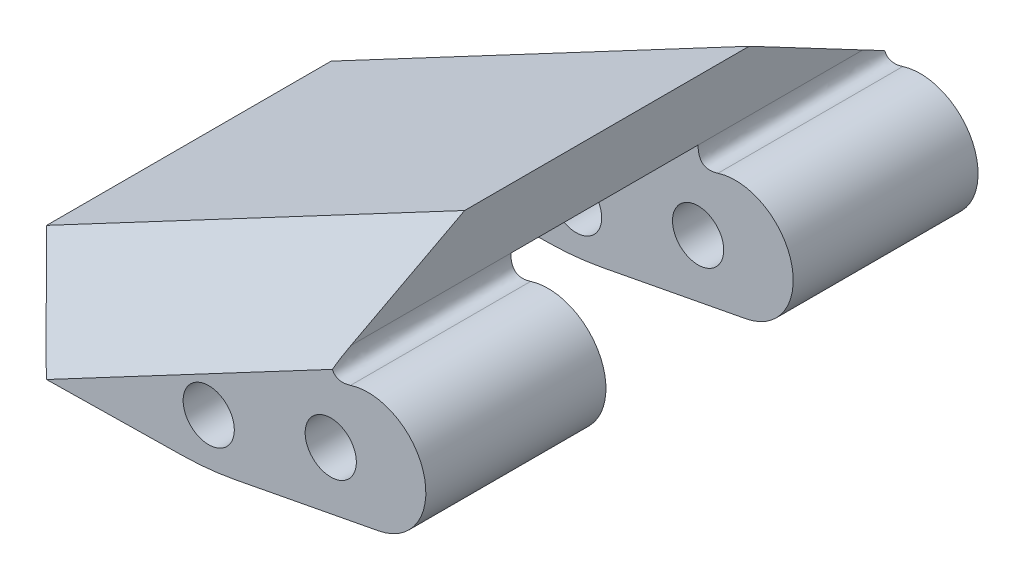
SolidWorks part; units mm, degrees
ref_plane "Front Plane" through (0, 0, 0) normal (0, 0, 1) x (1, 0, 0)
ref_plane "Top Plane" through (0, 0, 0) normal (0, 1, 0) x (1, 0, 0)
ref_plane "Right Plane" through (0, 0, 0) normal (1, 0, 0) x (0, 0, -1)
sketch "Sketch1" plane through (0, 0, 0) normal (0, 0, 1) x (1, 0, 0)
  line L0 (12.7, 6.7412) -> (0, 0) construction
  line L1 (0, 0) -> (6.5194, 0.1021)
  line L2 (8.7012, 0.3257) -> (62.1596, 10.5279) construction
  line L3 (12.7, 6.7412) -> (12.7, 9.2412)
  line L4 (12.7, 9.2412) -> (-4.7099, 0)
  line L5 (-4.7099, 0) -> (0, 0)
  line L6 (8.7012, 0.3257) -> (14.7032, 1.4711)
  circle A0 centre (12.7, 3.4818) radius 1.0668
  circle A1 centre (7.6176, 2.1057) radius 1.0668
  arc A2 (13.5262, 6.1356) -> (14.7032, 1.4711) centre (14.2515, 3.8379) cw
  parabola Q0 (13.5262, 6.1356) -> (12.7, 6.7412) focus (13.0175, 6.308) apex (12.9065, 6.1566)
  parabola Q1 (6.5194, 0.1021) -> (8.7012, 0.3257) focus (6.9702, 6.4599) apex (7.6152, 0.1666)
  point P0 (0, 0)
  dimension "D1" = 2.5
  dimension "D2" = 13.5262
extrude "Boss-Extrude1" add sketch "Sketch1" along normal blind 7.5
sketch "Sketch2" plane through (0, 0, 0) normal (0, 0, -1) x (-1, 0, 0)
  line L0 (-12.7, 6.7412) -> (4.7099, 0)
  line L1 (4.7099, 0) -> (-12.7, 9.2412)
  line L2 (-12.7, 9.2412) -> (-12.7, 6.7412)
extrude "Boss-Extrude2" add sketch "Sketch2" along normal blind 7.8
sketch "Sketch3" plane through (0, 0, -7.8) normal (0, 0, -1) x (-1, 0, 0)
  line L5 (-12.7, 9.2412) -> (-12.7, 6.7412)
  line L6 (4.7099, 0) -> (-12.7, 9.2412)
  line L7 (0, 0) -> (4.7099, 0)
  line L8 (-6.5194, 0.1021) -> (0, 0)
  line L9 (-14.7032, 1.4711) -> (-8.7012, 0.3257)
  line L10 (-12.7, 9.2412) -> (-12.7, 6.7412)
  line L11 (4.7099, 0) -> (-12.7, 9.2412)
  line L12 (0, 0) -> (4.7099, 0)
  line L13 (-6.5194, 0.1021) -> (0, 0)
  line L14 (-14.7032, 1.4711) -> (-8.7012, 0.3257)
  circle A0 centre (-12.7, 3.4818) radius 1.0668 construction
  arc A1 (-13.5262, 6.1356) -> (-14.7032, 1.4711) centre (-14.2515, 3.8379) ccw
  arc A2 (-13.5262, 6.1356) -> (-14.7032, 1.4711) centre (-14.2515, 3.8379) ccw
  circle A3 centre (-12.7, 3.4818) radius 1.0668
  circle A4 centre (-7.6176, 2.1057) radius 1.0668 construction
  circle A5 centre (-7.6176, 2.1057) radius 1.0668
  parabola Q2 (-12.7, 6.7412) -> (-13.5262, 6.1356) focus (-13.0175, 6.308) apex (-12.9065, 6.1566)
  parabola Q3 (-8.7012, 0.3257) -> (-6.5194, 0.1021) focus (-6.9702, 6.4599) apex (-7.6152, 0.1666)
  parabola Q4 (-12.7, 6.7412) -> (-13.5262, 6.1356) focus (-13.0175, 6.308) apex (-12.9065, 6.1566)
  parabola Q5 (-8.7012, 0.3257) -> (-6.5194, 0.1021) focus (-6.9702, 6.4599) apex (-7.6152, 0.1666)
  dimension "D1" = 0
extrude "Boss-Extrude3" add sketch "Sketch3" along normal blind 7.7
sketch "Sketch4" plane through (0, 0, 7.5) normal (0, 0, 1) x (1, 0, 0)
  line L2 (-4.7099, 0) -> (12.7, 6.7412) construction
  line L3 (0, 0) -> (6.5194, 0.1021) construction
  line L4 (-4.7099, 0) -> (0, 0) construction
  line L5 (0, 0) -> (4.638, 0.0726)
  line L6 (-4.7099, 0) -> (0, 0)
  line L7 (-4.7099, 0) -> (3.9951, 3.3706) construction
  line L8 (-4.7099, 0) -> (3.9951, 4.6206)
  line L9 (12.7, 9.2412) -> (-4.7099, 0) construction
  line L10 (3.9951, 4.6206) -> (3.9951, 3.3706)
  arc A0 (3.9951, 3.3706) -> (4.638, 0.0726) centre (4.6113, 1.7791) ccw
extrude "Boss-Extrude4" add sketch "Sketch4" against normal up to surface (23 mm away) up to face at (11.6332, 3.4818, -15.5)
chamfer "Chamfer1" distance 2.6 angle 65 2 edges at (3.9951, 4.6206, 7.5) (3.9951, 4.6206, -15.5)
